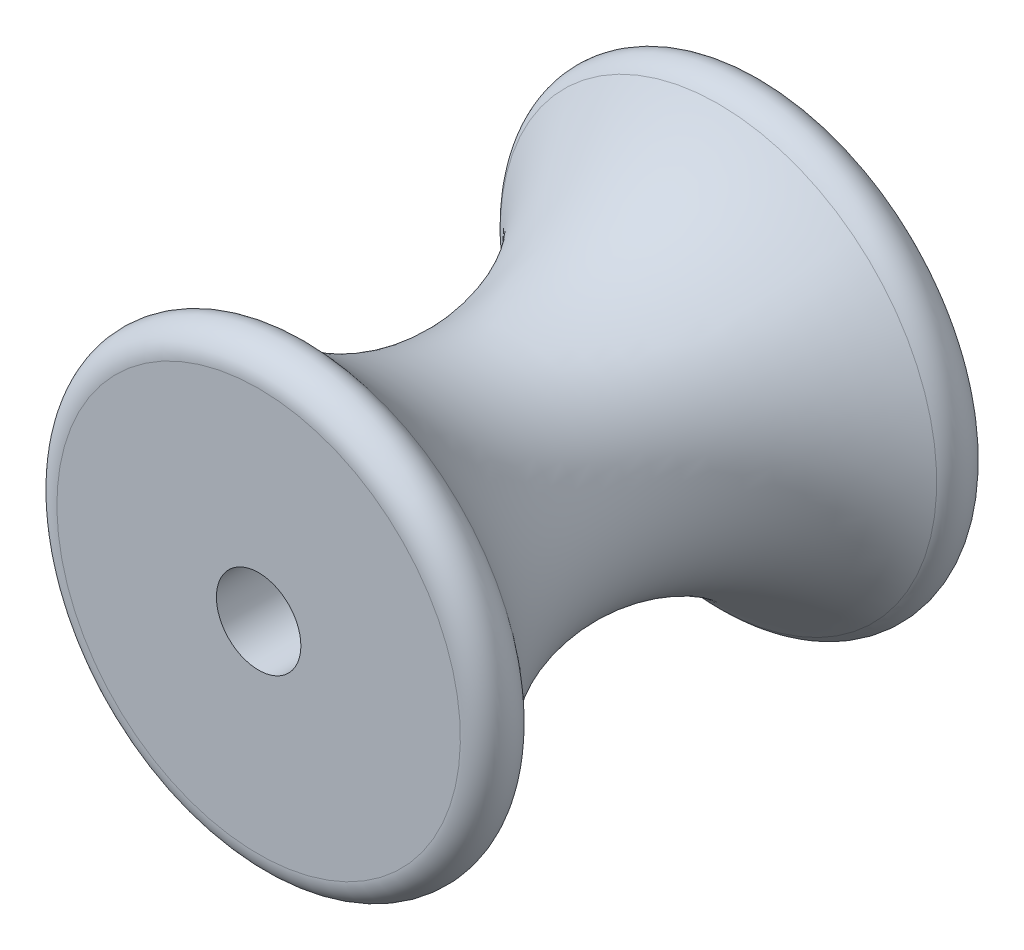
SolidWorks part; units mm, degrees
ref_plane "Front Plane" through (0, 0, 0) normal (0, 0, 1) x (1, 0, 0)
ref_plane "Top Plane" through (0, 0, 0) normal (0, 1, 0) x (1, 0, 0)
ref_plane "Right Plane" through (0, 0, 0) normal (1, 0, 0) x (0, 0, -1)
sketch "Sketch1" plane through (0, 0, 0) normal (1, 0, 0) x (0, 0, -1)
  line L0 (10, 0) -> (-10, 0) construction
  line L1 (7.0683, 13.3135) -> (14.3379, -19.6991) construction
  line L2 (10, 1.6) -> (-10, 1.6) construction
  line L4 (0, 55) -> (0, -55) construction
  line L5 (10, 1.6) -> (10, 14.5) construction
  line L6 (-10, 1.6) -> (-10, 14.5) construction
  line L7 (9.6, 1.6) -> (9.6, 11.7)
  line L8 (-9.6, 1.6) -> (-9.6, 11.7)
  line L9 (9.6, 1.6) -> (-9.6, 1.6)
  line L11 (10, 16.5) -> (10, -25.2482) construction
  circle A0 centre (0, 14.5) radius 10 construction
  arc A1 (9.6, 11.7) -> (-9.6, 11.7) centre (0, 14.5) cw
  point P2 (0, 0)
  dimension "D1" = 0.8
revolve "Revolve1" add sketch "Sketch1" angle 360 about L0
fillet "Fillet1" radius 1 2 edges at (0, 11.7, 9.6) (0, 11.7, -9.6)
